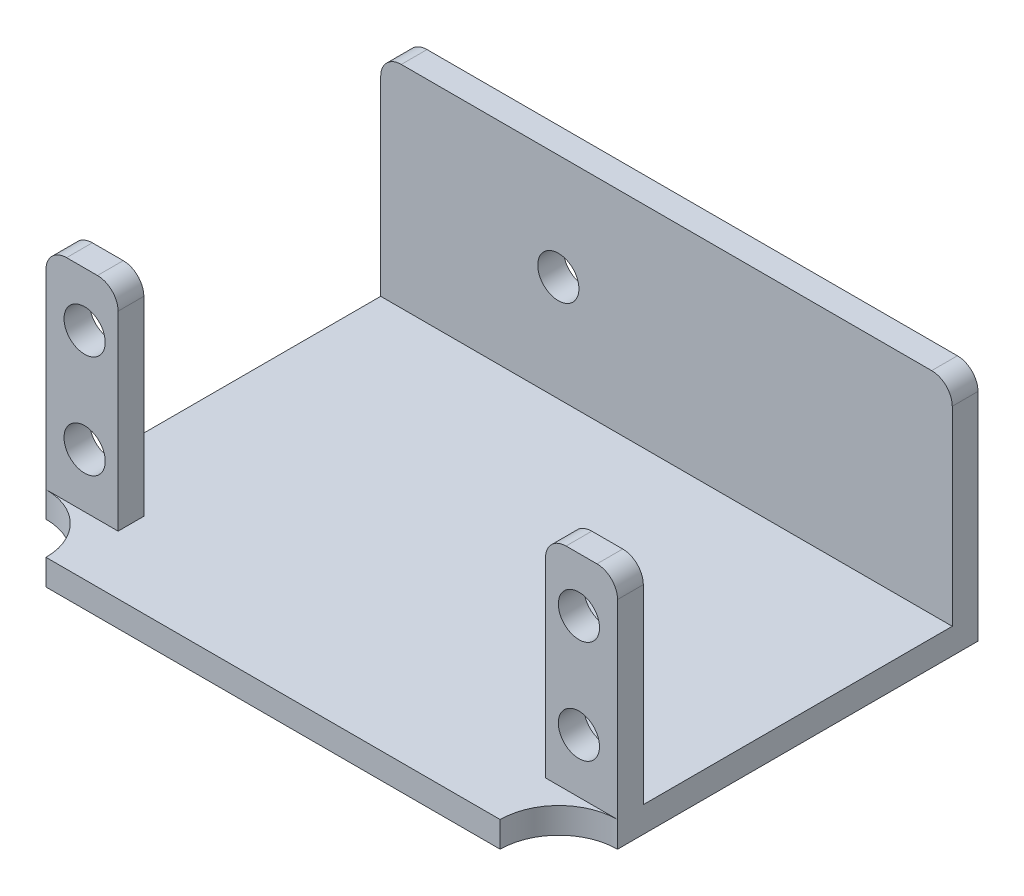
SolidWorks part; units mm, degrees
ref_plane "Front" through (0, 0, 0) normal (0, 0, 1) x (1, 0, 0)
ref_plane "Top" through (0, 0, 0) normal (0, 1, 0) x (1, 0, 0)
ref_plane "Right" through (0, 0, 0) normal (1, 0, 0) x (0, 0, -1)
sketch "Sketch1" plane through (0, 0, 0) normal (0, 1, 0) x (1, 0, 0)
  line L1 (0, 0) -> (55.5, 0)
  line L2 (0, 0) -> (0, 38.2)
  line L3 (0, 38.2) -> (55.5, 38.2)
  line L4 (55.5, 0) -> (55.5, 38.2)
  dimension "D1" = 38.2
  dimension "D2" = 55.5
extrude "bracketBase" add sketch "Sketch1" along normal blind 2.5
ref_plane "referencePlane1" through (0, 0, -8.2) normal (0, 0, 1) x (1, 0, 0)
sketch "Sketch2" plane through (0, 0, -8.2) normal (0, 0, 1) x (1, 0, 0)
  line L0 (27.75, 2.5) -> (27.75, 23) construction
  line L1 (0, 2.5) -> (7, 2.5)
  line L2 (0, 2.5) -> (0, 23)
  line L3 (0, 23) -> (7, 23)
  line L4 (7, 2.5) -> (7, 23)
  line L5 (0, 2.5) -> (55.5, 2.5) construction
  line L6 (55.5, 23) -> (48.5, 23)
  line L7 (48.5, 2.5) -> (48.5, 23)
  line L8 (55.5, 2.5) -> (48.5, 2.5)
  line L9 (55.5, 2.5) -> (55.5, 23)
  dimension "D1" = 20.5
  dimension "D2" = 7
extrude "servoMountingHoleTabs" add sketch "Sketch2" along normal blind 2.5
sketch "Sketch3" plane through (0, 0, -5.7) normal (0, 0, 1) x (1, 0, 0)
  line L0 (0, 12.75) -> (7, 12.75) construction
  line L3 (0, 23) -> (0, 2.5) construction
  line L4 (7, 2.5) -> (7, 23) construction
  line L5 (7, 23) -> (0, 23) construction
  line L6 (27.75, 2.5) -> (27.75, 23) construction
  line L7 (0, 2.5) -> (55.5, 2.5) construction
  circle A0 centre (3.75, 17.75) radius 2
  circle A1 centre (3.75, 7.75) radius 2
  circle A2 centre (51.75, 7.75) radius 2
  circle A3 centre (51.75, 17.75) radius 2
  dimension "D1" = 4
  dimension "D2" = 3.75
  dimension "D3" = 5.25
extrude "servoMountingHoles" cut sketch "Sketch3" against normal blind 2.5
sketch "Sketch4" plane through (0, 0, 0) normal (0, 1, 0) x (1, 0, 0)
  line L0 (55.5, 8.2) -> (55.5, 38.2) construction
  line L1 (0, 38.2) -> (55.5, 38.2)
  line L2 (0, 38.2) -> (0, 40.7)
  line L3 (0, 40.7) -> (55.5, 40.7)
  line L4 (55.5, 38.2) -> (55.5, 40.7)
  dimension "D1" = 2.5
extrude "baseWall" add sketch "Sketch4" along normal up to surface (23 mm away) up to face at (3.5, 23, -6.95)
sketch "Sketch6" plane through (0, 2.5, 0) normal (0, 1, 0) x (1, 0, 0)
  circle A0 centre (0, 0) radius 5.7
  circle A1 centre (55.5, 0) radius 5.7
extrude "baseTrim" cut sketch "Sketch6" against normal blind 2.5
fillet "Fillet1" radius 2 6 edges at (7, 23, -6.95) (48.5, 23, -6.95) (0, 23, -6.95) (55.5, 23, -6.95) (55.5, 23, -39.45) (0, 23, -39.45)
sketch "Sketch7" plane through (0, 0, -40.7) normal (0, 0, -1) x (-1, 0, 0)
  line L0 (0, 21) -> (0, 0) construction
  line L1 (-55.5, 0) -> (0, 0) construction
  circle A0 centre (-17.25, 12.75) radius 2
  dimension "D1" = 4
  dimension "D2" = 17.25
  dimension "D3" = 12.75
extrude "M4mountingHole" cut sketch "Sketch7" against normal blind 10
